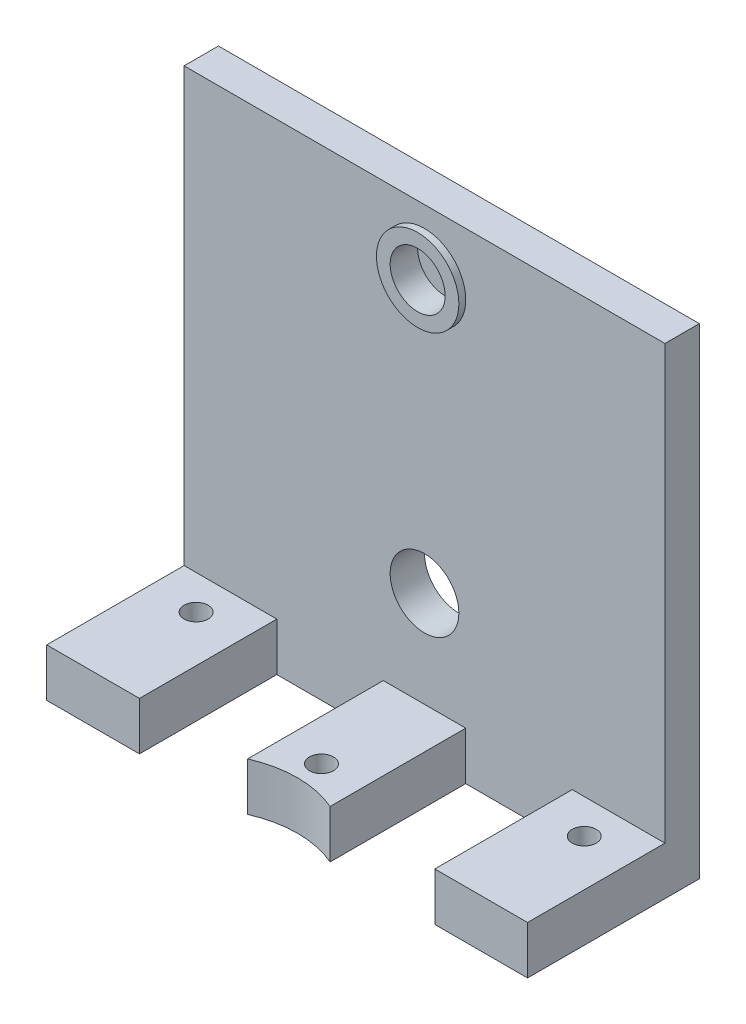
SolidWorks part; units mm, degrees
ref_plane "Front Plane" through (0, 0, 0) normal (0, 0, 1) x (1, 0, 0)
ref_plane "Top Plane" through (0, 0, 0) normal (0, 1, 0) x (1, 0, 0)
ref_plane "Right Plane" through (0, 0, 0) normal (1, 0, 0) x (0, 0, -1)
sketch "Sketch1" plane through (0, 0, 0) normal (0, 0, 1) x (1, 0, 0)
  line L1 (-35, 35) -> (35, 35)
  line L2 (-35, 35) -> (-35, -35)
  line L3 (-35, -35) -> (35, -35)
  line L4 (35, 35) -> (35, -35)
  line L5 (-35, 35) -> (35, -35) construction
  line L6 (-35, -35) -> (35, 35) construction
  circle A1 centre (0, -14) radius 5
  point P0 (0, 0)
  dimension "D4" = 10
  dimension "D1" = 70
  dimension "D5" = 21
  dimension "D6" = 70
extrude "Boss-Extrude1" add sketch "Sketch1" along normal blind 5
sketch "Sketch2" plane through (0, 0, 5) normal (0, 0, 1) x (1, 0, 0)
  line L0 (-35, -35) -> (35, -35) construction
  line L1 (-35, -35) -> (-21.5, -35)
  line L2 (-35, -35) -> (-35, -28)
  line L3 (-35, -28) -> (-21.5, -28)
  line L4 (-21.5, -35) -> (-21.5, -28)
  line L5 (35, -35) -> (21.5, -35)
  line L6 (35, -35) -> (35, -28)
  line L7 (35, -28) -> (21.5, -28)
  line L8 (21.5, -35) -> (21.5, -28)
  line L9 (-6, -28) -> (6, -28)
  line L10 (-6, -28) -> (-6, -35)
  line L11 (-6, -35) -> (6, -35)
  line L12 (6, -28) -> (6, -35)
  line L13 (-6, -28) -> (6, -35) construction
  line L14 (-6, -35) -> (6, -28) construction
  point P10 (0, -31.5)
  point P17 (0, -35)
  dimension "D1" = 7
  dimension "D2" = 7
  dimension "D3" = 43
  dimension "D4" = 12
  dimension "D5" = 7
extrude "Boss-Extrude2" add sketch "Sketch2" along normal blind 20
sketch "Sketch3" plane through (0, -28, 0) normal (0, 1, 0) x (1, 0, 0)
  line L1 (-21.5, -5) -> (-35, -5) construction
  line L4 (-28.25, -5) -> (-28.25, -19) construction
  line L5 (0, -5) -> (0, -14.1237) construction
  line L6 (6, -5) -> (-6, -5) construction
  line L7 (28.25, -5) -> (28.25, -19) construction
  line L8 (6, -25) -> (-6, -25) construction
  line L11 (-21.5, -25) -> (-35, -25) construction
  circle A0 centre (-28.25, -10) radius 1.75
  circle A1 centre (28.25, -10) radius 1.75
  circle A2 centre (0, -20) radius 1.75
  point P19 (0, -25)
  dimension "D1" = 3.5
  dimension "D3" = 3.5
  dimension "D2" = 5
  dimension "D4" = 5
extrude "Cut-Extrude1" cut sketch "Sketch3" against normal blind 20
sketch "Sketch4" plane through (0, 0, 5) normal (0, 0, 1) x (1, 0, 0)
  line L0 (35, 35) -> (-35, 35) construction
  circle A0 centre (0, 26) radius 4
  point P2 (0, 35)
  dimension "D1" = 8
  dimension "D2" = 9
extrude "Cut-Extrude2" cut sketch "Sketch4" against normal blind 3
sketch "Sketch5" plane through (0, 0, 5) normal (0, 0, 1) x (1, 0, 0)
  circle A0 centre (0, 26) radius 4
  circle A1 centre (0, 26) radius 6
  dimension "D1" = 12
extrude "Boss-Extrude3" add sketch "Sketch5" along normal blind 1
sketch "Sketch6" plane through (0, -35, 0) normal (0, -1, 0) x (1, 0, 0)
  line L0 (6, 25) -> (-6, 25) construction
  circle A0 centre (0, 38.5) radius 15
  point P2 (0, 25)
  dimension "D1" = 30
  dimension "D2" = 13.5
extrude "Cut-Extrude3" cut sketch "Sketch6" against normal through all
